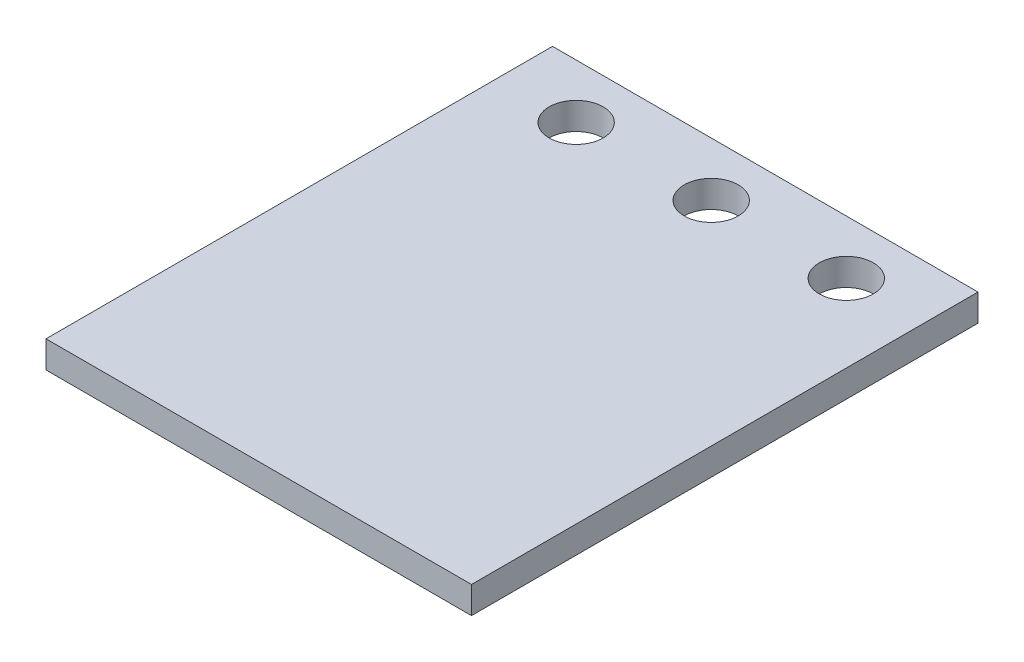
SolidWorks part; units mm, degrees
ref_plane "Alzado" through (0, 0, 0) normal (0, 0, 1) x (1, 0, 0)
ref_plane "Planta" through (0, 0, 0) normal (0, 1, 0) x (1, 0, 0)
ref_plane "Vista lateral" through (0, 0, 0) normal (1, 0, 0) x (0, 0, -1)
ref_plane "Plano1" through (0, 0, 360) normal (0, 0, -1) x (-1, 0, 0)
sketch "Croquis2" plane through (0, 0, 360) normal (0, 0, -1) x (-1, 0, 0)
  line L0 (7.7541, 182.0598) -> (7.7541, 202.8344) construction
  line L1 (192.7541, 202.8344) -> (-177.2459, 202.8344) construction
  line L2 (7.7541, 202.8344) -> (7.7541, 222.538) construction
  line L3 (-149.7459, 202.8344) -> (165.2541, 202.8344)
  line L4 (-149.7459, 202.8344) -> (-149.7459, 182.8344)
  line L5 (-149.7459, 182.8344) -> (165.2541, 182.8344)
  line L6 (165.2541, 202.8344) -> (165.2541, 182.8344)
  point P4 (7.7541, 182.0598)
  dimension "D1" = 315
  dimension "D2" = 20
extrude "Saliente-Extruir1" add sketch "Croquis2" along normal blind 375
sketch "Croquis3" plane through (0, 202.8344, 0) normal (0, 1, 0) x (1, 0, 0)
  line L0 (-7.7541, 15) -> (-7.7541, -25) construction
  line L1 (-165.2541, 15) -> (149.7459, 15) construction
  circle A0 centre (-107.7541, -25) radius 20
  circle A1 centre (-7.7541, -25) radius 20
  circle A2 centre (92.2459, -25) radius 20
  point P7 (-7.7541, -5)
  dimension "D3" = 40
  dimension "D1" = 20
  dimension "D4" = 100
  dimension "D2" = 3
extrude "Cortar-Extruir1" cut sketch "Croquis3" against normal up to next
